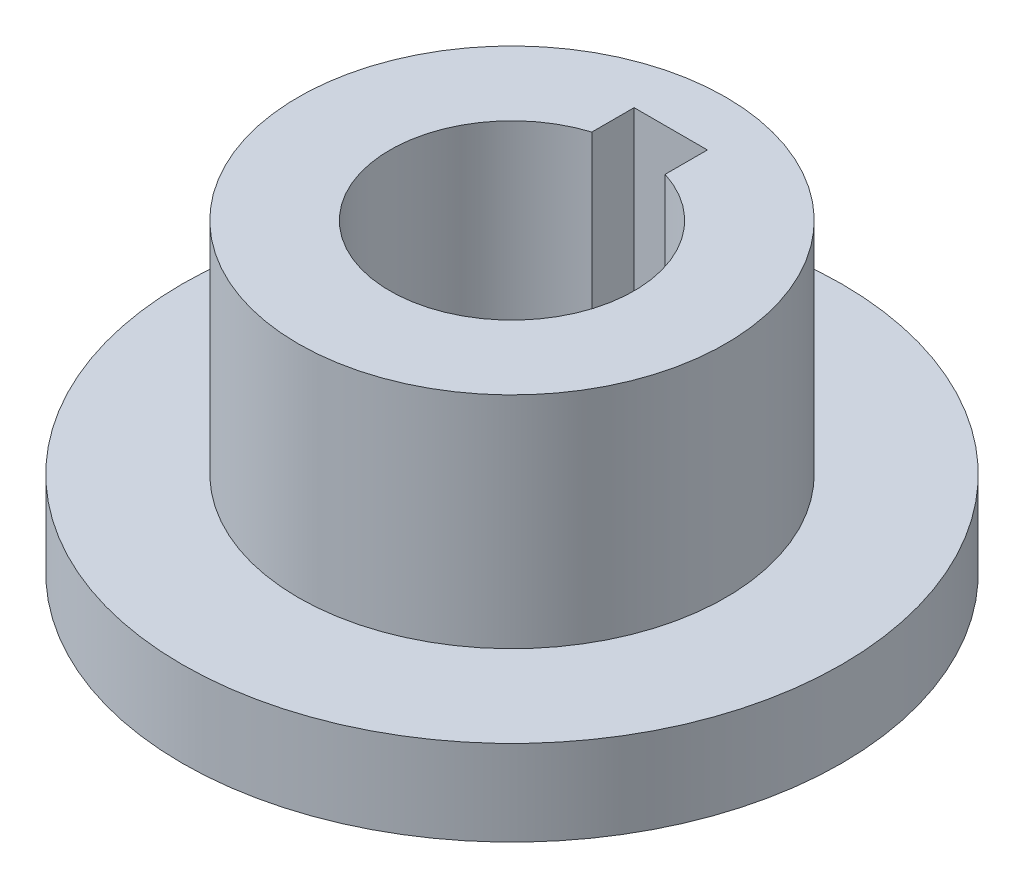
SolidWorks part; units mm, degrees
ref_plane "前视基准面" through (0, 0, 0) normal (0, 0, 1) x (1, 0, 0)
ref_plane "上视基准面" through (0, 0, 0) normal (0, 1, 0) x (1, 0, 0)
ref_plane "右视基准面" through (0, 0, 0) normal (1, 0, 0) x (0, 0, -1)
sketch "草图1" plane through (0, 0, 0) normal (0, 0, 1) x (1, 0, 0)
  line L0 (0, 92.8571) -> (0, 0) construction
  line L1 (0, 0) -> (85.2303, 0) construction
  line L2 (10, 0) -> (27, 0)
  line L3 (27, 0) -> (27, 7)
  line L4 (27, 7) -> (17.5, 7)
  line L5 (17.5, 7) -> (17.5, 25)
  line L6 (17.5, 25) -> (10, 25)
  line L7 (10, 25) -> (10, 0)
  dimension "D1" = 17.5
  dimension "D2" = 7.5
  dimension "D3" = 25
  dimension "D4" = 18
  dimension "D5" = 27
revolve "旋转1" add sketch "草图1" angle 360 about L0
sketch "草图2" plane through (0, 25, 0) normal (0, 1, 0) x (1, 0, 0)
  line L0 (0, 27) -> (0, 0) construction
  line L1 (0, 0) -> (35.227, 0) construction
  line L3 (3, 4.0979) -> (-3, 4.0979)
  line L4 (3, 4.0979) -> (3, 13)
  line L5 (3, 13) -> (-3, 13)
  line L6 (-3, 4.0979) -> (-3, 13)
  line L7 (3, 4.0979) -> (-3, 13) construction
  line L8 (3, 13) -> (-3, 4.0979) construction
  circle A0 centre (0, 0) radius 27 construction
  circle A1 centre (0, 0) radius 17.5 construction
  point P5 (0, 8.5489)
  point P14 (0, 17.5)
  dimension "D1" = 6
  dimension "D3" = 4.5
extrude "切除-拉伸1" cut sketch "草图2" against normal through all
